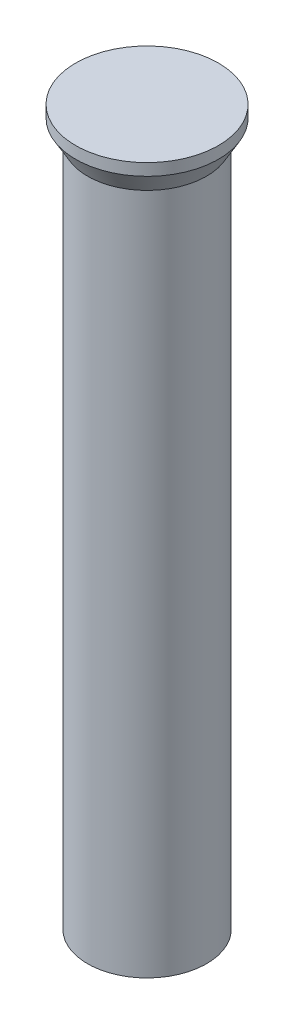
SolidWorks part; units mm, degrees
ref_plane "Front Plane" through (0, 0, 0) normal (0, 0, 1) x (1, 0, 0)
ref_plane "Top Plane" through (0, 0, 0) normal (0, 1, 0) x (1, 0, 0)
ref_plane "Right Plane" through (0, 0, 0) normal (1, 0, 0) x (0, 0, -1)
sketch "Sketch1" plane through (0, 0, 0) normal (0, 0, 1) x (1, 0, 0)
  line L0 (0, 0) -> (6, 0)
  line L1 (6, 0) -> (6, -1)
  line L2 (6, -1) -> (5, -2.7321)
  line L3 (5, -2.7321) -> (5, -60)
  line L4 (5, -60) -> (0, -60)
  line L5 (0, -60) -> (0, 0)
  line L6 (0, -65) -> (0, 5) construction
  dimension "Length" = 60
  dimension "D2" = 5
  dimension "D3" = 5
  dimension "Punch Dia" = 10
  dimension "Head Dia" = 12
  dimension "K" = 1
  dimension "D7" = 30
revolve "Revolve1" add sketch "Sketch1" angle 360 about L6
